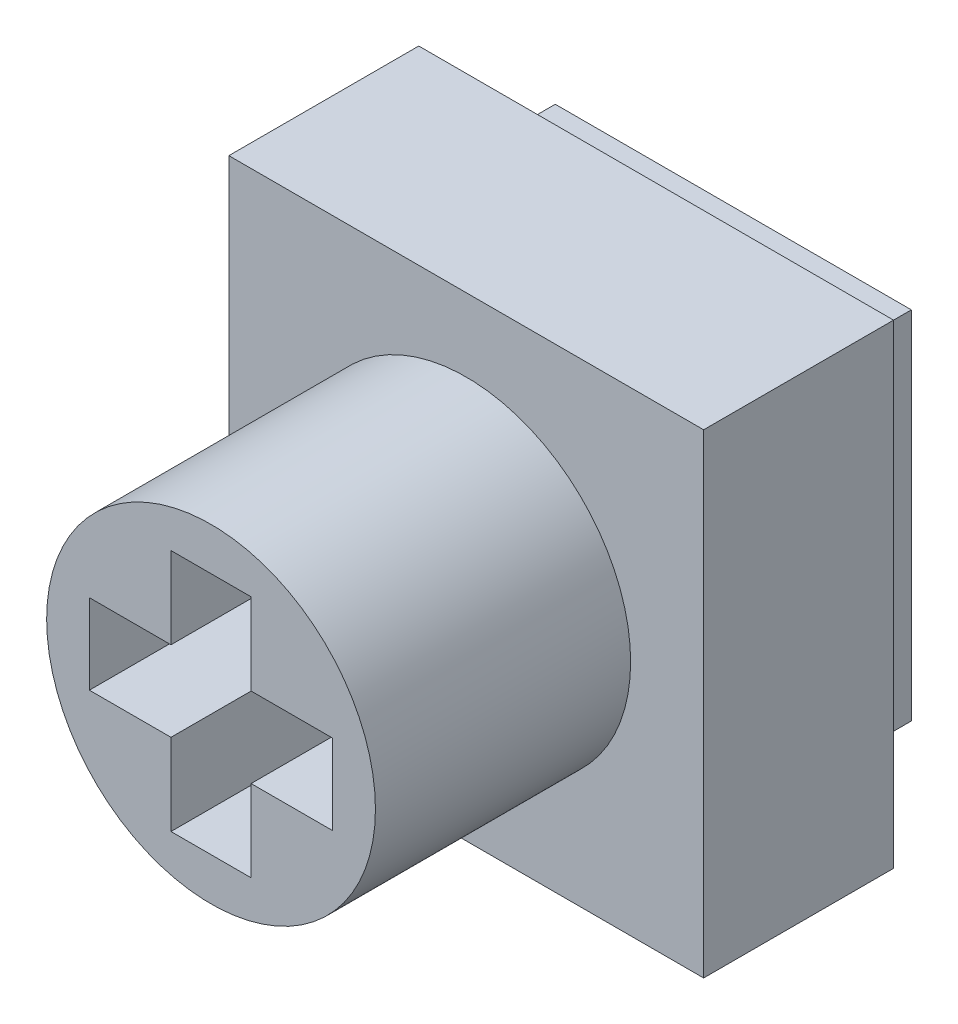
SolidWorks part; units mm, degrees
ref_plane "Front Plane" through (0, 0, 0) normal (0, 0, 1) x (1, 0, 0)
ref_plane "Top Plane" through (0, 0, 0) normal (0, 1, 0) x (1, 0, 0)
ref_plane "Right Plane" through (0, 0, 0) normal (1, 0, 0) x (0, 0, -1)
sketch "Sketch6" plane through (0, 4.1325, 0) normal (0, 0, 1) x (-1, 0, 0)
  line L1 (2.0476, 26.5232) -> (-2.0524, 26.5232)
  line L2 (2.0476, 26.5232) -> (2.0476, 27.8732)
  line L3 (2.0476, 27.8732) -> (-2.0524, 27.8732)
  line L4 (-2.0524, 26.5232) -> (-2.0524, 27.8732)
  line L5 (2.0476, 26.5232) -> (-2.0524, 27.8732) construction
  line L6 (2.0476, 27.8732) -> (-2.0524, 26.5232) construction
  line L7 (-0.6774, 29.2482) -> (0.6726, 29.2482)
  line L8 (-0.6774, 29.2482) -> (-0.6774, 25.1482)
  line L9 (-0.6774, 25.1482) -> (0.6726, 25.1482)
  line L10 (0.6726, 29.2482) -> (0.6726, 25.1482)
  line L11 (-0.6774, 29.2482) -> (0.6726, 25.1482) construction
  line L12 (-0.6774, 25.1482) -> (0.6726, 29.2482) construction
  line L13 (-2.7724, 24.4282) -> (2.7676, 24.4282)
  line L14 (-2.7724, 24.4282) -> (-2.7724, 29.9682)
  line L15 (-2.7724, 29.9682) -> (2.7676, 29.9682)
  line L16 (2.7676, 24.4282) -> (2.7676, 29.9682)
  line L17 (-2.7724, 24.4282) -> (2.7676, 29.9682) construction
  line L18 (-2.7724, 29.9682) -> (2.7676, 24.4282) construction
  circle A0 centre (-0.0024, 27.1982) radius 2.77
  point P0 (-0.0024, 27.1982)
  point P5 (-0.0024, 27.1982)
  point P16 (0, 0)
  point P17 (0, 0)
  dimension "D5" = 5.54
  dimension "D1" = 1.35
  dimension "D2" = 4.1
  dimension "D3" = 1.35
  dimension "D4" = 4.1
  dimension "D6" = 5.54
  dimension "D7" = 5.54
extrude "Boss-Extrude1" add sketch "Sketch6" along normal blind 7.5 contours A0 L7 L10 L3 L2 L1 L9 L8 L4
sketch "Sketch7" plane through (0, 0, 0) normal (0, 0, 1) x (-1, 0, 0)
  line L0 (-0.0024, 23.0657) -> (2.7676, 23.0657) construction
  line L2 (-4.0024, 19.0657) -> (3.9976, 19.0657)
  line L3 (-4.0024, 19.0657) -> (-4.0024, 27.0657)
  line L4 (-4.0024, 27.0657) -> (3.9976, 27.0657)
  line L5 (3.9976, 19.0657) -> (3.9976, 27.0657)
  line L6 (-4.0024, 19.0657) -> (3.9976, 27.0657) construction
  line L7 (-4.0024, 27.0657) -> (3.9976, 19.0657) construction
  dimension "D1" = 8
  dimension "D2" = 8
extrude "Boss-Extrude2" add sketch "Sketch7" along normal blind 3.2
sketch "Sketch8" plane through (0, 0, 0) normal (0, 0, -1) x (-1, 0, 0)
  line L0 (-0.0024, -19.0657) -> (-0.0024, -27.0657) construction
  line L1 (-4.0024, -19.0657) -> (3.9976, -19.0657) construction
  line L2 (3.9976, -27.0657) -> (-4.0024, -27.0657) construction
  line L4 (2.9976, -20.0657) -> (-3.0024, -20.0657)
  line L5 (2.9976, -20.0657) -> (2.9976, -26.0657)
  line L6 (2.9976, -26.0657) -> (-3.0024, -26.0657)
  line L7 (-3.0024, -20.0657) -> (-3.0024, -26.0657)
  line L8 (2.9976, -20.0657) -> (-3.0024, -26.0657) construction
  line L9 (2.9976, -26.0657) -> (-3.0024, -20.0657) construction
  point P6 (-0.0024, -23.0657)
  dimension "D1" = 6
  dimension "D2" = 6
extrude "Boss-Extrude3" add sketch "Sketch8" along normal blind 1.3
